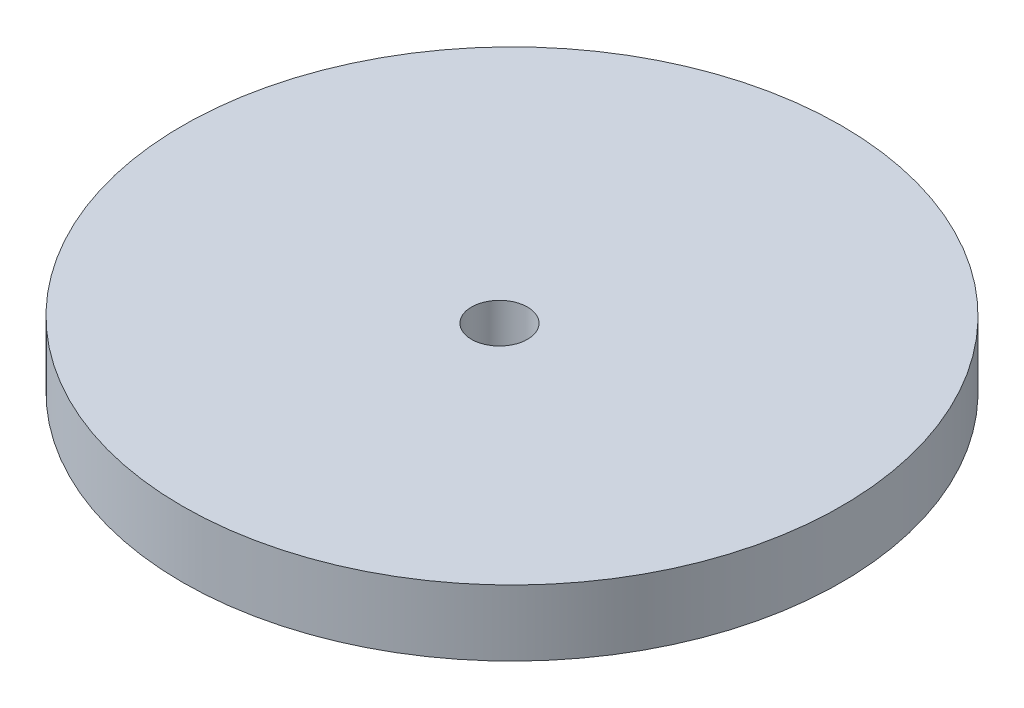
SolidWorks part; units mm, degrees
ref_plane "Front Plane" through (0, 0, 0) normal (0, 0, 1) x (1, 0, 0)
ref_plane "Top Plane" through (0, 0, 0) normal (0, 1, 0) x (1, 0, 0)
ref_plane "Right Plane" through (0, 0, 0) normal (1, 0, 0) x (0, 0, -1)
sketch "Sketch1" plane through (0, 0, 0) normal (0, 1, 0) x (1, 0, 0)
  circle A0 centre (0, 0) radius 100
  circle A1 centre (0, -3.8022) radius 8.5
  dimension "D1" = 200
  dimension "D2" = 17
extrude "Boss-Extrude1" add sketch "Sketch1" along normal blind 20
